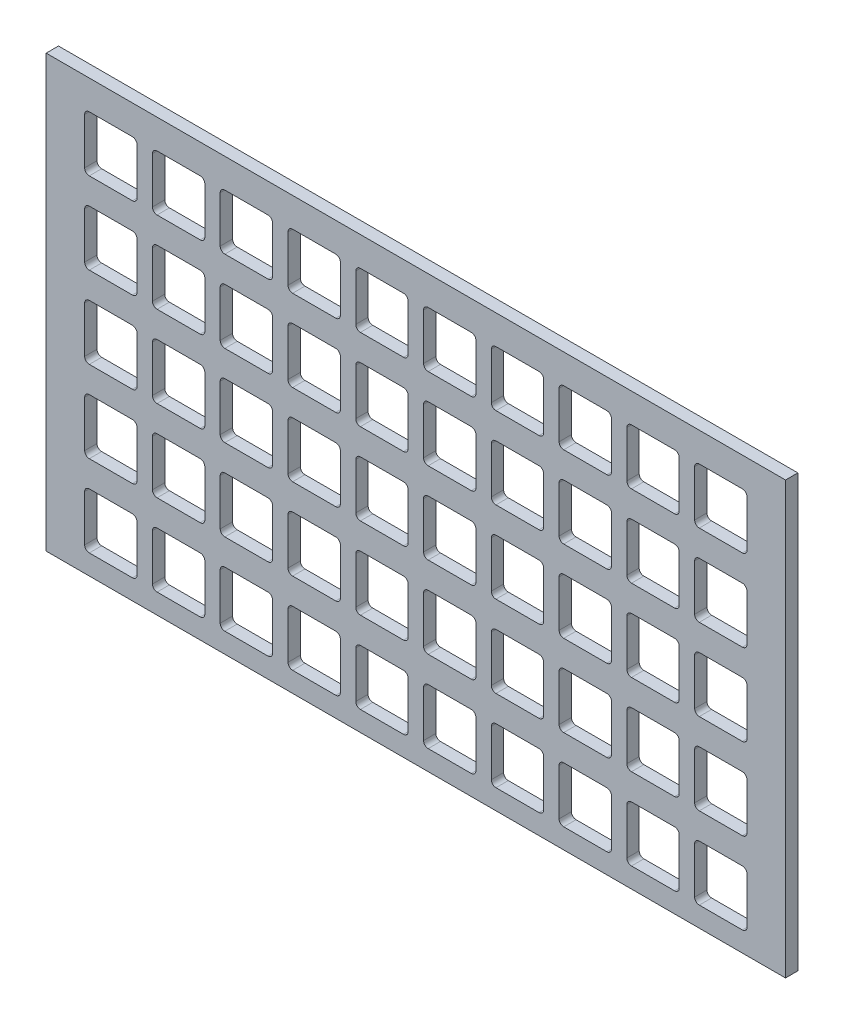
SolidWorks part; units mm, degrees
ref_plane "Front Plane" through (0, 0, 0) normal (0, 0, 1) x (1, 0, 0)
ref_plane "Top Plane" through (0, 0, 0) normal (0, 1, 0) x (1, 0, 0)
ref_plane "Right Plane" through (0, 0, 0) normal (1, 0, 0) x (0, 0, -1)
sketch "Sketch1" plane through (0, 0, 0) normal (0, 0, 1) x (1, 0, 0)
  line L1 (-120, 140) -> (120, 140)
  line L2 (-120, 140) -> (-120, 0)
  line L3 (-120, 0) -> (120, 0)
  line L4 (120, 140) -> (120, 0)
  line L5 (0, 140) -> (0, 0) construction
  dimension "D1" = 240
  dimension "D2" = 140
extrude "Boss-Extrude1" add sketch "Sketch1" along normal blind 4
sketch "Sketch2" plane through (0, 0, 4) normal (0, 0, 1) x (1, 0, 0)
  line L0 (-120, 7.5) -> (120, 7.5) construction
  line L1 (-18.5, 23.5) -> (-3.5, 23.5) construction
  line L2 (-18.5, 23.5) -> (-18.5, 7.5) construction
  line L3 (-18.5, 7.5) -> (-3.5, 7.5) construction
  line L4 (-3.5, 23.5) -> (-3.5, 7.5) construction
  line L5 (-120, 140) -> (-120, 0) construction
  line L6 (120, 0) -> (120, 140) construction
  line L7 (-18, 6.5) -> (-4, 6.5)
  line L8 (-2.5, 23) -> (-2.5, 8)
  line L9 (-18, 24.5) -> (-4, 24.5)
  line L10 (-19.5, 23) -> (-19.5, 8)
  line L11 (-120, 0) -> (120, 0) construction
  line L12 (-19.5, 6.5) -> (-2.5, 6.5) construction
  line L13 (-2.5, 24.5) -> (-2.5, 6.5) construction
  line L14 (-19.5, 24.5) -> (-2.5, 24.5) construction
  line L15 (-19.5, 24.5) -> (-19.5, 6.5) construction
  arc A0 (-4, 6.5) -> (-2.5, 8) centre (-4, 8) ccw
  arc A1 (-2.5, 23) -> (-4, 24.5) centre (-4, 23) ccw
  arc A2 (-18, 24.5) -> (-19.5, 23) centre (-18, 23) ccw
  arc A3 (-18, 6.5) -> (-19.5, 8) centre (-18, 8) cw
  point P10 (-11, 23.5)
  dimension "D6" = 1.5
  dimension "D1" = 15
  dimension "D2" = 16
  dimension "D3" = 11
  dimension "D5" = 7.5
  dimension "D4" = 1
extrude "Hole" cut sketch "Sketch2" against normal through all
pattern_linear "LPattern1" count 5 spacing 22 along (-1, 0, 0) count 6 spacing 22 along (1, 0, 0) of "Hole"
pattern_linear "LPattern2" count 5 spacing 26.5 along (0, 1, 0) of "LPattern1", "Hole"
